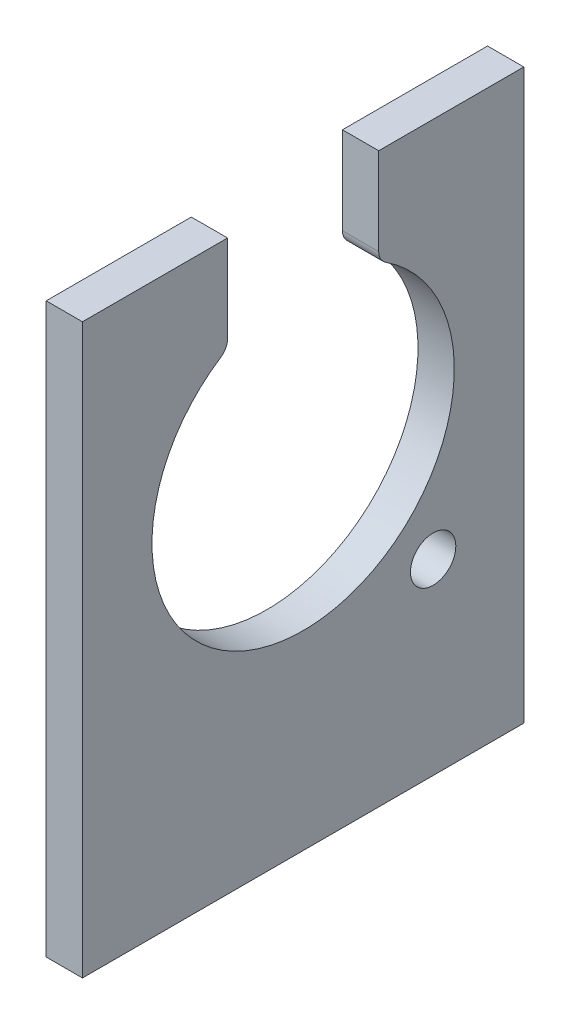
SolidWorks part; units mm, degrees
ref_plane "Front Plane" through (0, 0, 0) normal (0, 0, 1) x (1, 0, 0)
ref_plane "Top Plane" through (0, 0, 0) normal (0, 1, 0) x (1, 0, 0)
ref_plane "Right Plane" through (0, 0, 0) normal (1, 0, 0) x (0, 0, -1)
sketch "Sketch1" plane through (0, 0, 0) normal (1, 0, 0) x (0, 0, -1)
  line L0 (0, 0) -> (0, 94) construction
  line L1 (73, 94) -> (25, 94)
  line L2 (73, 94) -> (73, -94)
  line L3 (73, -94) -> (-73, -94)
  line L4 (-73, 94) -> (-73, -94)
  line L5 (73, 94) -> (-73, -94) construction
  line L6 (73, -94) -> (-73, 94) construction
  line L7 (-25, 94) -> (-25, 65.0977)
  line L8 (25, 94) -> (25, 65.0977)
  line L9 (-25, 94) -> (-73, 94)
  arc A0 (-27.2727, 60.907) -> (27.2727, 60.907) centre (0, 19) ccw
  arc A1 (25, 65.0977) -> (27.2727, 60.907) centre (30, 65.0977) ccw
  arc A2 (-25, 65.0977) -> (-27.2727, 60.907) centre (-30, 65.0977) cw
  point P0 (0, 0)
  point P20 (25, 62.3013)
  point P23 (-25, 62.3013)
  dimension "D3" = 100
  dimension "D6" = 5
  dimension "D1" = 188
  dimension "D2" = 146
  dimension "D4" = 75
  dimension "D5" = 25
extrude "Boss-Extrude1" add sketch "Sketch1" along normal blind 12
sketch "Sketch2" plane through (12, 0, 0) normal (1, 0, 0) x (0, 0, -1)
  line L0 (73, -94) -> (73, 94) construction
  line L1 (-73, -94) -> (73, -94) construction
  circle A0 centre (43, -32) radius 7.5
  dimension "D3" = 15
  dimension "D1" = 30
  dimension "D2" = 62
extrude "Cut-Extrude1" cut sketch "Sketch2" against normal through all
